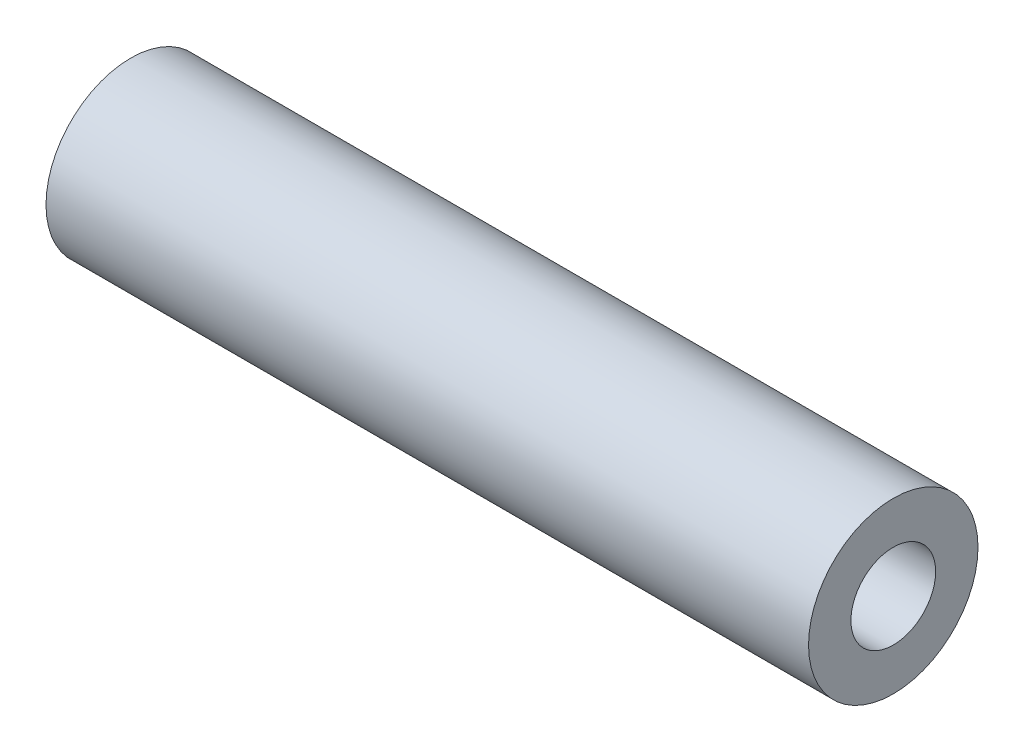
SolidWorks part; units mm, degrees
ref_plane "Front Plane" through (0, 0, 0) normal (0, 0, 1) x (1, 0, 0)
ref_plane "Top Plane" through (0, 0, 0) normal (0, 1, 0) x (1, 0, 0)
ref_plane "Right Plane" through (0, 0, 0) normal (1, 0, 0) x (0, 0, -1)
sketch "Sketch1" plane through (0, 0, 0) normal (1, 0, 0) x (0, 0, -1)
  circle A0 centre (0, 0) radius 12.7
  circle A1 centre (0, 0) radius 6.35
  dimension "D1" = 25.4
  dimension "D2" = 12.7
extrude "Boss-Extrude1" add sketch "Sketch1" along normal blind 114.3
